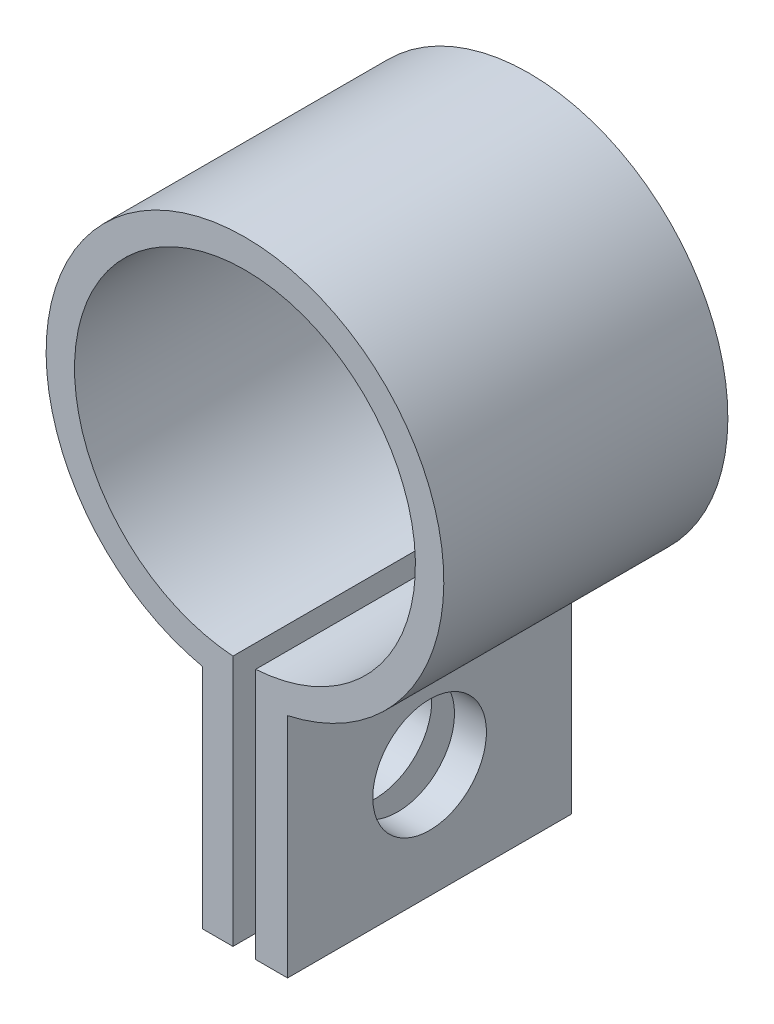
SolidWorks part; units mm, degrees
ref_plane "Front Plane" through (0, 0, 0) normal (0, 0, 1) x (1, 0, 0)
ref_plane "Top Plane" through (0, 0, 0) normal (0, 1, 0) x (1, 0, 0)
ref_plane "Right Plane" through (0, 0, 0) normal (1, 0, 0) x (0, 0, -1)
sketch "Sketch1" plane through (0, 0, 0) normal (0, 0, 1) x (1, 0, 0)
  line L1 (1.5, -14.8374) -> (-1.5, -14.8374)
  line L2 (1.5, -14.8374) -> (1.5, -6.8374)
  line L4 (-1.5, -14.8374) -> (-1.5, -6.8374)
  line L5 (1.5, -14.8374) -> (-0.3023, -5.4204) construction
  line L6 (-0.4091, -9.1376) -> (-1.5, -14.8374) construction
  arc A0 (1.5, -6.8374) -> (-1.5, -6.8374) centre (0, 0) ccw
  circle A1 centre (0, 0) radius 6
  point P4 (0, -7)
  dimension "D1" = 14
  dimension "D2" = 12
  dimension "D4" = 3
  dimension "D5" = 8
extrude "Boss-Extrude1" add sketch "Sketch1" along normal mid plane 10
sketch "Sketch2" plane through (0, 0, 5) normal (0, 0, 1) x (1, 0, 0)
  line L0 (55, 0) -> (-55, 0) construction
  line L1 (-0.4232, 0) -> (0.3766, 0)
  line L2 (-0.4232, 0) -> (-0.4232, -15.1855)
  line L3 (-0.4232, -15.1855) -> (0.3766, -15.1855)
  line L4 (0.3766, 0) -> (0.3766, -15.1855)
extrude "Cut-Extrude1" cut sketch "Sketch2" against normal through all
hole_wizard "Ø4.0mm Dowel Hole1" positions "Sketch4" profile "Sketch5" hole size "Ø4.0" standard "ANSI Metric"
sketch "Sketch4" plane through (-1.5, 0, 0) normal (-1, 0, 0) x (0, 0, 1)
  line L0 (0, -44.2539) -> (0, 44.2539) construction
  line L1 (5, -14.8374) -> (-5, -14.8374) construction
  point P6 (0, -10.8374)
  point P7 (0, -10.8788)
  dimension "D1" = 4
sketch "Sketch5" plane through (-1.5, -10.8374, 0) normal (0, 1, 0) x (0, 0, 1)
  line L0 (0, 0) -> (0, 33.7017)
  line L1 (0, 33.7017) -> (2, 32.5)
  line L2 (2, 32.5) -> (2, 0)
  line L5 (2, 0) -> (0, 0)
  line L10 (0, 33.7017) -> (-2, 32.5) construction
  line L11 (0, -6.35) -> (0, 107.95) construction
  dimension "Hole Dia." = 4
  dimension "Hole Depth" = 32.5
  dimension "Drill Angle" = 118
